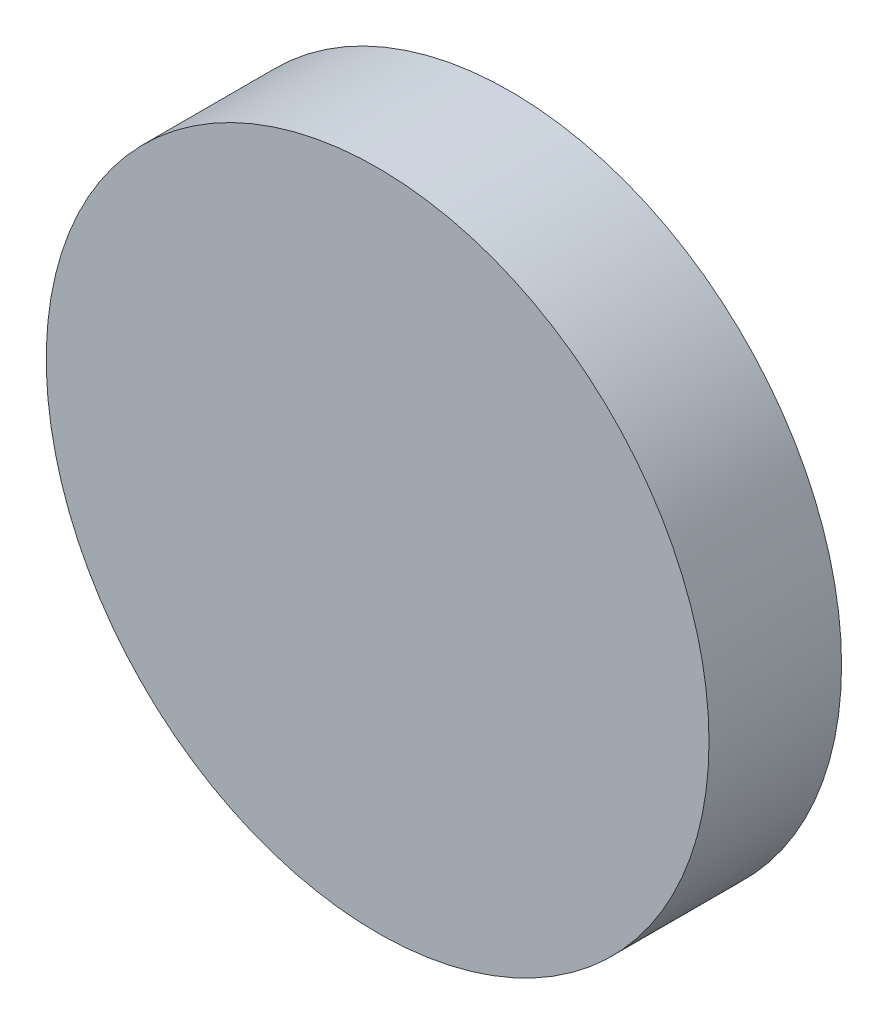
SolidWorks part; units mm, degrees
ref_plane "Front Plane" through (0, 0, 0) normal (0, 0, 1) x (1, 0, 0)
ref_plane "Top Plane" through (0, 0, 0) normal (0, 1, 0) x (1, 0, 0)
ref_plane "Right Plane" through (0, 0, 0) normal (1, 0, 0) x (0, 0, -1)
sketch "Sketch1" plane through (0, 0, 0) normal (0, 0, 1) x (1, 0, 0)
  circle A0 centre (0, 0) radius 31.75
  dimension "D1" = 63.5
extrude "Boss-Extrude1" add sketch "Sketch1" along normal mid plane 12.7
